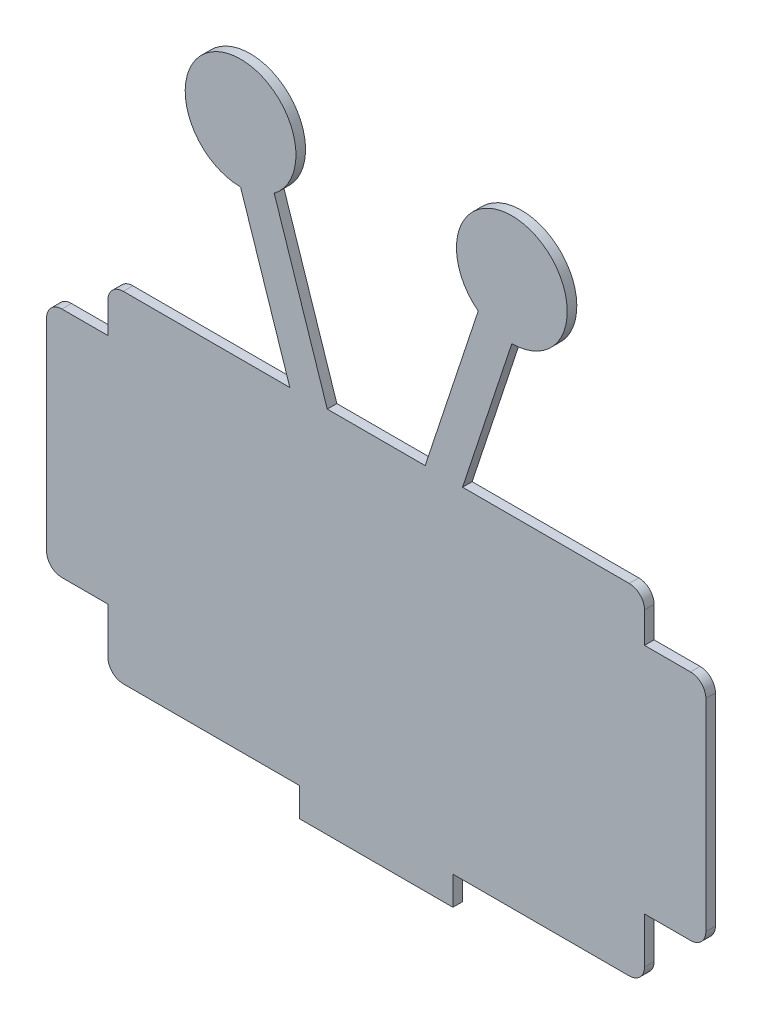
SolidWorks part; units mm, degrees
ref_plane "Front" through (0, 0, 0) normal (0, 0, 1) x (1, 0, 0)
ref_plane "Top" through (0, 0, 0) normal (0, 1, 0) x (1, 0, 0)
ref_plane "Right" through (0, 0, 0) normal (1, 0, 0) x (0, 0, -1)
sketch "Sketch1" plane through (0, 0, 0) normal (0, 0, 1) x (1, 0, 0)
  line L0 (83.82, -5.08) -> (83.82, 107.5436) construction
  line L1 (0, -5.08) -> (58.42, -5.08)
  line L2 (-5.08, 0) -> (-5.08, 15.24)
  line L3 (0, 107.5436) -> (55.2119, 107.5436)
  line L4 (172.72, 0) -> (172.72, 15.24)
  line L5 (-5.08, 51.2318) -> (172.72, 51.2318) construction
  line L6 (193.04, 20.32) -> (193.04, 87.2236)
  line L7 (-5.08, 15.24) -> (-20.32, 15.24)
  line L9 (-5.08, 92.3036) -> (-20.32, 92.3036)
  line L10 (-25.4, 20.32) -> (-25.4, 87.2236)
  line L11 (172.72, 92.3036) -> (187.96, 92.3036)
  line L13 (172.72, 15.24) -> (187.96, 15.24)
  line L14 (-5.08, 92.3036) -> (-5.08, 102.4636)
  line L15 (172.72, 92.3036) -> (172.72, 102.4636)
  line L16 (55.2119, 107.5436) -> (38.8791, 156.9121)
  line L17 (67.6077, 107.5436) -> (50.0264, 160.6859)
  line L18 (67.6077, 107.5436) -> (100.0323, 107.5436)
  line L19 (100.0323, 107.5436) -> (117.6136, 160.6859)
  line L20 (112.4281, 107.5436) -> (128.7609, 156.9121)
  line L21 (112.4281, 107.5436) -> (167.64, 107.5436)
  line L22 (109.22, -5.08) -> (167.64, -5.08)
  line L24 (58.42, -5.08) -> (58.42, -14.605)
  line L25 (58.42, -14.605) -> (109.22, -14.605)
  line L26 (109.22, -5.08) -> (109.22, -14.605)
  arc A0 (0, 107.5436) -> (-5.08, 102.4636) centre (0, 102.4636) ccw
  arc A1 (0, -5.08) -> (-5.08, 0) centre (0, 0) cw
  arc A2 (167.64, -5.08) -> (172.72, 0) centre (167.64, 0) ccw
  arc A3 (167.64, 107.5436) -> (172.72, 102.4636) centre (167.64, 102.4636) cw
  arc A4 (-20.32, 92.3036) -> (-25.4, 87.2236) centre (-20.32, 87.2236) ccw
  arc A5 (-25.4, 20.32) -> (-20.32, 15.24) centre (-20.32, 20.32) ccw
  arc A6 (187.96, 92.3036) -> (193.04, 87.2236) centre (187.96, 87.2236) cw
  arc A7 (193.04, 20.32) -> (187.96, 15.24) centre (187.96, 20.32) cw
  arc A8 (50.0264, 160.6859) -> (38.8791, 156.9121) centre (38.8791, 175.2628) ccw
  arc A9 (117.6136, 160.6859) -> (128.7609, 156.9121) centre (128.7609, 175.2628) cw
  point P38 (172.72, 7.62)
  dimension "D3" = 10.16
  dimension "D5" = 10.16
  dimension "D4" = 10.16
  dimension "D8" = 20.32
  dimension "D1" = 20.32
  dimension "D2" = 15.24
  dimension "D6" = 177.8
  dimension "D7" = 112.6236
  dimension "D9" = 9.525
  dimension "D10" = 50.8
  dimension "D11" = 63.5
extrude "Boss-Extrude1" add sketch "Sketch1" along normal blind 3.175
